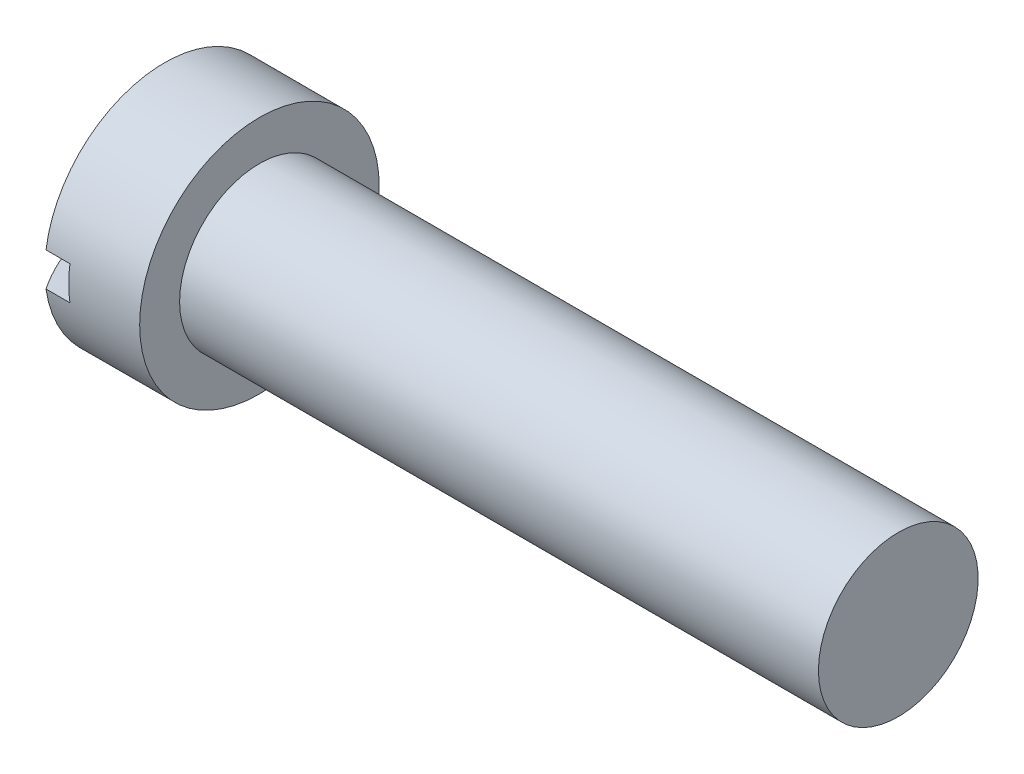
SolidWorks part; units mm, degrees
ref_plane "Plane1" through (0, 0, 0) normal (0, 0, 1) x (1, 0, 0)
ref_plane "Plane2" through (0, 0, 0) normal (0, 1, 0) x (1, 0, 0)
ref_plane "Plane3" through (0, 0, 0) normal (1, 0, 0) x (0, 0, -1)
sketch "BodySke" plane through (0, 0, 0) normal (0, 0, 1) x (1, 0, 0)
  line L0 (10.4648, 6.35) -> (10.4648, 9.525)
  line L1 (10.4648, 9.525) -> (2.921, 9.525)
  line L2 (-25.4, 0) -> (127, 0) construction
  line L3 (61.2648, 0) -> (0, 0)
  line L4 (10.4648, 6.35) -> (61.2648, 6.35)
  line L5 (61.2648, 6.35) -> (61.2648, 0)
  line L6 (10.4648, -9.525) -> (2.921, -9.525) construction
  line L7 (10.4648, -6.35) -> (61.2648, -6.35) construction
  line L8 (11.7348, 1.2192) -> (11.7348, -0.4698) construction
  line L9 (10.4648, 1.2192) -> (10.4648, -0.4698) construction
  arc A0 (0, 0) -> (2.921, 9.525) centre (16.9904, 0) cw
  dimension "Diameter" = 12.7
  dimension "Head_dia" = 19.05
  dimension "Head_ht" = 10.4648
  dimension "Length" = 50.8
  dimension "Head_side_ht" = 7.5438
  dimension "Thread_nom" = 50.8
  dimension "Advance" = 1.27
revolve "Base-Revolve" add sketch "BodySke" angle 360 about L2
cosmetic thread "ThreadCosmetic" parameters "Thread_length"=49.53, "Thread_minor"=11.1887
sketch "Sketch2" plane through (0, 0, 0) normal (1, 0, 0) x (0, 0, -1)
  line L0 (-9.525, -1.3462) -> (-9.525, 1.3462)
  line L1 (-9.525, 1.3462) -> (9.525, 1.3462)
  line L2 (9.525, 1.3462) -> (9.525, -1.3462)
  line L3 (9.525, -1.3462) -> (-9.525, -1.3462)
  dimension "D1" = 19.05
  dimension "D2" = 9.525
  dimension "D3" = 1.3462
  dimension "Slot_width" = 2.6924
extrude "Slot" cut sketch "Sketch2" along normal blind 4.826
sketch "Sketch3" plane through (0, 0, 0) normal (1, 0, 0) x (0, 0, -1)
  line L0 (1.1557, -7.1374) -> (-1.1557, -7.1374)
  line L1 (1.1557, -7.1374) -> (1.1557, 7.1374)
  line L2 (-1.1557, 7.1374) -> (1.1557, 7.1374)
  line L3 (-1.1557, 7.1374) -> (-1.1557, -7.1374)
  dimension "Cross_width" = 2.3114
  dimension "D1" = 1.1557
  dimension "Cross_dia" = 14.2748
  dimension "D2" = 7.1374
ref_plane "Plane4" through (8.6106, 0, 0) normal (1, 0, 0) x (0, 0, -1)
sketch "Sketch4" plane through (8.6106, 0, 0) normal (1, 0, 0) x (0, 0, -1)
  line L0 (0.5778, -0.5778) -> (-0.5778, -0.5779)
  line L1 (0.5778, -0.5778) -> (0.5778, 0.5778)
  line L2 (-0.5778, 0.5778) -> (0.5778, 0.5778)
  line L3 (-0.5778, 0.5778) -> (-0.5778, -0.5779)
  dimension "D1" = 1.1557
  dimension "D3" = 1.1557
  dimension "D4" = 0.5778
loft "Cross" [suppressed] cut profiles "Sketch3", "Sketch4"
pattern_circular "CirPattern1" [suppressed] count 2 every 90 about axis through (-25.4, 0, 0) along (1, 0, 0)
sketch "Sketch5" plane through (0, 0, 0) normal (0, 1, 0) x (1, 0, 0)
  line L4 (-25.4, 0) -> (127, 0) construction
  line L5 (10.4648, -6.312) -> (10.4648, 6.3337) construction
  circle A0 centre (7.2709, 0) radius 0.889
  dimension "Drilled_hole_dia" = 1.778
  dimension "D1" = 10.4648
  dimension "Drilled_hole_loc" = 3.1939
extrude "Hole" [suppressed] cut sketch "Sketch5" against normal through all and the other way through all
sketch "ThdSchSke" plane through (0, 0, 0) normal (0, 0, 1) x (1, 0, 0)
  line L0 (11.7348, -5.5943) -> (11.2057, -6.35)
  line L1 (11.7348, -5.5943) -> (12.2639, -6.35)
  line L2 (12.2639, -6.35) -> (12.2639, -7.9375)
  line L3 (-3.175, 0) -> (5.1513, 0) construction
  line L5 (12.2639, -7.9375) -> (11.2057, -7.9375)
  line L6 (11.2057, -7.9375) -> (11.2057, -6.35)
  dimension "Diameter" = 12.7
  dimension "SideAngle" = 55
  dimension "VeeAngle" = 70
  dimension "Thread_minor" = 11.1887
  dimension "Overcut" = 15.875
  dimension "Start" = 11.7348
revolve "ThreadSchematic" [suppressed] cut sketch "ThdSchSke" angle 360 about L3
pattern_linear "ThdSchPat" [suppressed]
equation "\"D1@Sketch3\" = \"Cross_width@Sketch3\" / 2"
equation "\"D2@Sketch3\" = \"Cross_dia@Sketch3\" / 2"
equation "\"D1@Sketch4\" = \"Cross_width@Sketch3\"*.5"
equation "\"D2@Sketch4\" = \"D1@Sketch4\" / 2"
equation "\"D3@Sketch4\" = \"D1@Sketch4\""
equation "\"D4@Sketch4\" = \"D2@Sketch4\""
equation "\"D1@Sketch2\" = \"Head_dia@BodySke\""
equation "\"D2@Sketch2\" = \"D1@Sketch2\" / 2"
equation "\"D3@Sketch2\" = \"Slot_width@Sketch2\" / 2"
equation "\"D1@Sketch5\" = \"Head_ht@BodySke\""
equation "\"Thread_length@ThreadCosmetic\" = ((sgn( (\"Length@BodySke\" - \"Advance@BodySke\" ) - \"Thread_nom@BodySke\" )-1)*( (\"Length@BodySke\" - \"Advance@BodySke\" ) - \"Thread_nom@BodySke\" ))/-2+ \"Thread_nom@BodySke\""
equation "\"Thread_minor@ThdSchSke\" = \"Thread_minor@ThreadCosmetic\""
equation "\"Diameter@ThdSchSke\" = \"Diameter@BodySke\""
equation "\"Overcut@ThdSchSke\" = \"Diameter@BodySke\" * 1.25"
equation "\"Start@ThdSchSke\" = \"Head_ht@BodySke\" + \"Length@BodySke\" - \"Thread_length@ThreadCosmetic\"  '---Non-countersunk---"
equation "\"Num_threads@ThdSchPat\" = int( \"Thread_length@ThreadCosmetic\" / \"Advance@BodySke\" + 0.999 )  + 1"
equation "\"Advance@ThdSchPat\" = \"Thread_length@ThreadCosmetic\" /  (\"Num_threads@ThdSchPat\" - 1) 'relax it"
